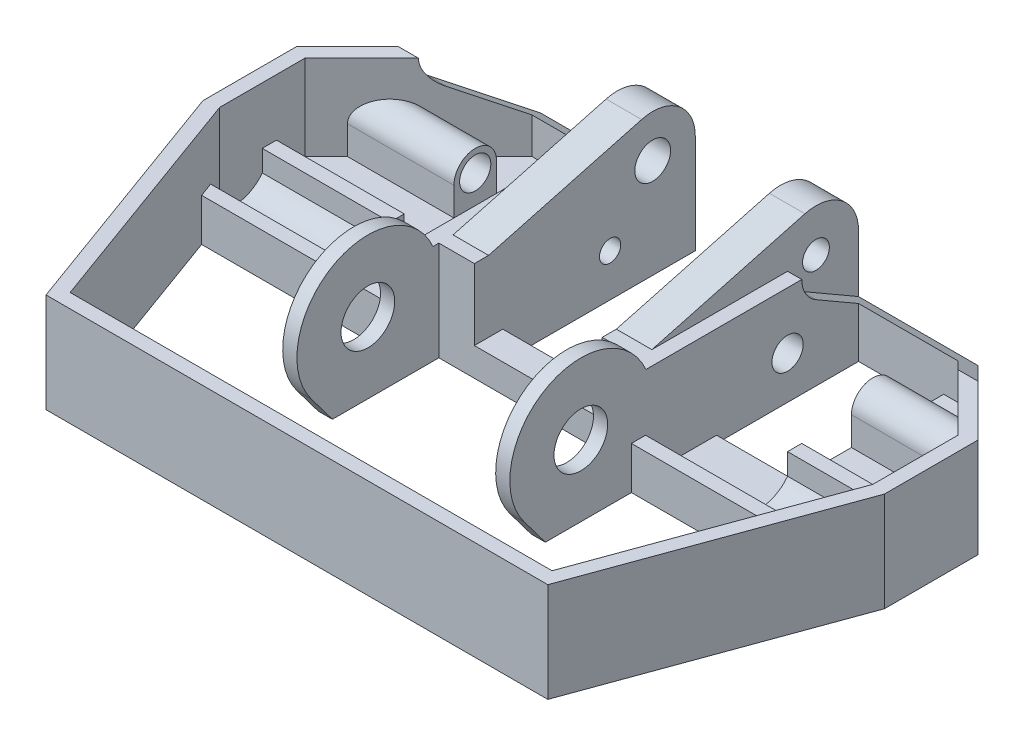
SolidWorks part; units mm, degrees
material "ABS"
ref_plane "Front Plane" through (0, 0, 0) normal (0, 0, 1) x (1, 0, 0)
ref_plane "Top Plane" through (0, 0, 0) normal (0, 1, 0) x (1, 0, 0)
ref_plane "Right Plane" through (0, 0, 0) normal (1, 0, 0) x (0, 0, -1)
sketch "Sketch1" plane through (0, 0, 0) normal (1, 0, 0) x (0, 0, -1)
  line L0 (9.525, -22.225) -> (9.525, 0)
  line L1 (-2.4719, 9.1987) -> (-36.703, 0)
  line L2 (-36.703, 0) -> (-36.703, -22.225)
  line L3 (-36.703, -22.225) -> (9.525, -22.225)
  circle A0 centre (0, 0) radius 20.6375 construction
  arc A1 (9.525, 0) -> (-2.4719, 9.1987) centre (0, 0) ccw
  point P5 (-31.75, -9.7269)
  point P10 (0, -20.6375)
  dimension "D1" = 41.275
  dimension "D2" = 9.525
  dimension "D3" = 22.225
  dimension "D4" = 46.228
  dimension "D5" = 1.5875
extrude "Boss-Extrude1" add sketch "Sketch1" along normal mid plane 44.45
ref_plane "Plane1" through (0, 0, 0) normal (0, -1, 0) x (-1, 0, 0)
sketch "Sketch3" plane through (0, 0, 0) normal (0, -1, 0) x (-1, 0, 0)
  line L0 (22.225, 9.525) -> (22.225, -36.703)
  line L1 (22.225, -36.703) -> (-22.225, -36.703)
  line L2 (-22.225, -36.703) -> (-22.225, 9.525)
  line L3 (-22.225, 9.525) -> (-48.9401, 9.525)
  line L4 (-48.9401, 9.525) -> (-76.2, -17.7349)
  line L5 (-76.2, -17.7349) -> (-76.2, -38.6598)
  line L6 (-76.2, -38.6598) -> (-56.1113, -93.853)
  line L7 (-56.1113, -93.853) -> (56.1113, -93.853)
  line L8 (56.1113, -93.853) -> (76.2, -38.6598)
  line L9 (76.2, -38.6598) -> (76.2, -17.7349)
  line L10 (76.2, -17.7349) -> (48.9401, 9.525)
  line L11 (48.9401, 9.525) -> (22.225, 9.525)
  line L12 (73.025, -19.05) -> (47.625, 6.35)
  line L13 (47.625, 6.35) -> (25.4, 6.35)
  line L14 (25.4, 6.35) -> (25.4, -49.403)
  line L15 (22.225, -39.878) -> (-22.225, -39.878)
  line L16 (-25.4, -49.403) -> (-25.4, 6.35)
  line L17 (-25.4, 6.35) -> (-47.625, 6.35)
  line L18 (-47.625, 6.35) -> (-73.025, -19.05)
  line L19 (-73.025, -19.05) -> (-73.025, -38.1)
  line L20 (-73.025, -38.1) -> (-53.8882, -90.678)
  line L21 (-53.8882, -90.678) -> (53.8882, -90.678)
  line L22 (-25.4, -49.403) -> (-22.225, -49.403)
  line L23 (73.025, -38.1) -> (73.025, -19.05)
  line L24 (22.225, -49.403) -> (25.4, -49.403)
  line L27 (22.225, -39.878) -> (22.225, -49.403)
  line L28 (-22.225, -39.878) -> (-22.225, -49.403)
  line L30 (25.4, -39.878) -> (-25.4, -39.878) construction
  line L31 (53.8882, -90.678) -> (73.025, -38.1)
  line L32 (53.8882, -90.678) -> (73.025, -38.1) construction
  line L34 (-73.025, -38.1) -> (-53.8882, -90.678) construction
  line L35 (25.4, 6.35) -> (25.4, -39.878) construction
  line L36 (-25.4, -39.878) -> (-25.4, 6.35) construction
  point P5 (0, -93.853)
  point P21 (0, 0)
  dimension "D1" = 20
  dimension "D2" = 22.225
  dimension "D3" = 3.175
  dimension "D4" = 47.625
  dimension "D5" = 50.8
  dimension "D6" = 9.525
  dimension "D8" = 44.45
  dimension "D9" = 45
extrude "Boss-Extrude2" add sketch "Sketch3" along normal up to surface (22.225 mm away) up to face at (0, -22.225, 13.589)
sketch "Sketch4" plane through (0, -22.225, 0) normal (0, -1, 0) x (1, 0, 0)
  line L0 (48.9401, -9.525) -> (-48.9401, -9.525) construction
  line L1 (-14.2875, -9.525) -> (14.2875, -9.525)
  line L2 (-14.2875, -9.525) -> (-14.2875, 33.528)
  line L3 (-14.2875, 33.528) -> (14.2875, 33.528)
  line L4 (14.2875, -9.525) -> (14.2875, 33.528)
  line L5 (22.225, 39.878) -> (-22.225, 39.878) construction
  point P6 (0, 33.528)
  dimension "D1" = 28.575
  dimension "D2" = 6.35
extrude "Cut-Extrude1" cut sketch "Sketch4" against normal through all
sketch "Sketch5" plane through (0, 0, 0) normal (1, 0, 0) x (0, 0, -1)
  line L0 (6.35, -22.225) -> (6.35, 0) construction
  line L1 (-17.7349, -22.225) -> (9.525, -22.225) construction
  circle A0 centre (-9.525, -12.7) radius 3.175
  point P6 (0, 0)
  dimension "D1" = 6.35
  dimension "D2" = 15.875
  dimension "D3" = 9.525
sketch "Sketch6" plane through (0, 0, 0) normal (0, 1, 0) x (1, 0, 0)
  line L0 (-22.225, 9.525) -> (-22.225, -2.4719) construction
  line L1 (-22.225, 4) -> (17.775, 4)
  line L2 (22.225, -2.4719) -> (22.225, 9.525) construction
  line L3 (-22.225, 0) -> (22.225, 0)
  line L4 (17.775, 4) -> (17.775, 3)
  line L5 (22.225, -2.4719) -> (22.225, 9.525) construction
  line L6 (-47.625, 6.35) -> (-25.4, 6.35) construction
  line L7 (-22.225, 0) -> (-88.5794, 0)
  line L8 (17.775, 3) -> (22.225, 3)
  line L10 (-22.225, 4) -> (-22.225, 6.35)
  line L11 (-22.225, 6.35) -> (-88.5794, 6.35)
  line L12 (-88.5794, 0) -> (-88.5794, 6.35)
  line L14 (22.225, 0) -> (78.8074, 0)
  line L15 (22.225, 3) -> (22.225, 6.35)
  line L16 (22.225, 6.35) -> (78.8074, 6.35)
  line L17 (78.8074, 0) -> (78.8074, 6.35)
  line L18 (25.4, 6.35) -> (47.625, 6.35) construction
  point P1 (0, 0)
  point P9 (0, 0)
  point P19 (-25.4294, 9.525)
  point P20 (-25.4, 0)
  point P21 (-25.4, 6.35)
  point P22 (-64.9741, 0)
  point P23 (-58.4654, -0.0002)
  point P24 (22.225, 0)
  point P25 (22.225, 9.525)
  point P28 (0, 0)
  point P29 (-113.2509, 0)
  point P30 (108.8149, 0)
  point P31 (25.4, 0)
  point P32 (37.9723, 6.35)
  point P35 (58.5203, -0.0552)
  point P36 (-25.4, 6.35)
  point P37 (-88.5794, 6.35)
  point P38 (60.3046, 0)
  point P39 (25.4, 0)
  point P40 (78.8074, 0)
  dimension "D1" = 4
  dimension "D2" = 3
  dimension "D3" = 40
revolve "Cut-Revolve1" cut sketch "Sketch6" angle 360 about L3
sketch "Sketch9" plane through (0, 0, 33.528) normal (0, 0, -1) x (-1, 0, 0)
  line L0 (-14.2875, 0.8532) -> (-14.2875, -15.875)
  line L1 (-14.2875, -15.875) -> (14.2875, -15.875)
  line L2 (14.2875, -15.875) -> (14.2875, 0.8532)
  line L3 (-14.2875, -22.225) -> (14.2875, -22.225) construction
  line L4 (14.2875, 0.8532) -> (-14.2875, 0.8532)
  point P8 (-11.652, -23.8125)
  dimension "D1" = 28.575
  dimension "D2" = 6.35
extrude "Cut-Extrude4" cut sketch "Sketch9" against normal up to next
sketch "Sketch10" plane through (25.4, 0, 0) normal (1, 0, 0) x (0, 0, -1)
  line L0 (-28.575, -17.4625) -> (-28.575, -12.7)
  line L1 (-41.275, -12.7) -> (-41.275, -17.4625)
  line L2 (6.35, -22.225) -> (6.35, 0) construction
  line L4 (-93.853, -22.225) -> (-38.6598, -22.225) construction
  line L5 (-44.45, -22.225) -> (-25.4, -22.225)
  line L6 (-44.45, -22.225) -> (-44.45, -12.7)
  line L7 (-44.45, -12.7) -> (-41.275, -12.7)
  line L8 (-25.4, -22.225) -> (-25.4, -12.7)
  line L9 (-28.575, -12.7) -> (-25.4, -12.7)
  arc A0 (-41.275, -17.4625) -> (-28.575, -17.4625) centre (-34.925, -12.7) ccw
  point P3 (0, 0)
  point P4 (-25.4, -26.0716)
  point P9 (-39.9499, -30.1625)
  point P10 (-38.1, -25.6652)
  point P11 (0, 0)
  dimension "D1" = 12.7
  dimension "D2" = 15.875
  dimension "D3" = 34.925
  dimension "D5" = 19.05
  dimension "D6" = 9.525
extrude "Boss-Extrude3" add sketch "Sketch10" along normal up to next
mirror "Mirror1" about plane through (0, 0, 0) normal (1, 0, 0) of "Boss-Extrude3"
sketch "Sketch11" plane through (0, -12.7, 0) normal (0, 1, 0) x (1, 0, 0)
  line L0 (-25.4, -28.575) -> (-25.4, -41.275) construction
  line L1 (-25.4, -34.925) -> (-44.45, -34.925)
  line L2 (-25.4, -34.925) -> (-25.4, -15.875)
  line L3 (-25.4, -15.875) -> (-44.45, -15.875)
  line L4 (-44.45, -34.925) -> (-44.45, -15.875)
  line L5 (25.4, -41.275) -> (25.4, -28.575) construction
  line L6 (25.4, -34.925) -> (44.45, -34.925)
  line L7 (25.4, -34.925) -> (25.4, -15.875)
  line L8 (25.4, -15.875) -> (44.45, -15.875)
  line L9 (44.45, -34.925) -> (44.45, -15.875)
  dimension "D1" = 19.05
extrude "Cut-Extrude5" cut sketch "Sketch11" against normal blind 7.9375
ref_plane "Plane2" through (0, -12.7, 0) normal (0, -1, 0) x (-1, 0, 0)
sketch "Sketch18" plane through (-44.45, 0, 0) normal (1, 0, 0) x (0, 0, -1)
  line L0 (-25.4, -22.225) -> (6.35, -22.225)
  line L1 (6.35, -22.225) -> (6.35, -19.05)
  line L2 (6.35, -22.225) -> (6.35, 0) construction
  line L3 (6.35, -19.05) -> (-4.7625, -19.05)
  line L4 (-4.7625, -19.05) -> (-4.7625, -12.7)
  line L5 (-56.8579, -12.7) -> (56.8579, -12.7) construction
  line L6 (-14.2875, -12.7) -> (-14.2875, -19.05)
  line L7 (-14.2875, -19.05) -> (-25.4, -19.05)
  line L8 (-25.4, -12.7) -> (-25.4, -22.225) construction
  line L9 (-25.4, -19.05) -> (-25.4, -22.225)
  arc A0 (-4.7625, -12.7) -> (-14.2875, -12.7) centre (-9.525, -12.7) ccw
  point P17 (-6.1927, -19.05)
  point P18 (-9.525, -12.7)
  dimension "D1" = 4.7625
  dimension "D2" = 3.175
extrude "Boss-Extrude6" add sketch "Sketch18" against normal up to next
mirror "Mirror3" about plane through (0, 0, 0) normal (1, 0, 0) of "Boss-Extrude6"
sketch "Sketch14" plane through (0, -12.7, 0) normal (0, -1, 0) x (-1, 0, 0)
  line L0 (-14.2875, 9.525) -> (-14.2875, -33.528) construction
  line L1 (-73.7019, -6.0325) -> (-19.05, -6.0325)
  line L2 (-73.7019, -6.0325) -> (-73.7019, -9.525)
  line L3 (-73.7019, -9.525) -> (-14.2875, -9.525)
  line L4 (-19.05, -6.0325) -> (-19.05, -7.1438)
  line L5 (0, 0) -> (0, 30.2993) construction
  line L6 (14.2875, -9.525) -> (14.2875, -7.1438)
  line L7 (-19.05, -7.1438) -> (-14.2875, -7.1438)
  line L8 (-14.2875, -9.525) -> (-14.2875, -7.1438)
  line L10 (19.05, -7.1438) -> (14.2875, -7.1438)
  line L11 (19.05, -6.0325) -> (19.05, -7.1438)
  line L12 (73.7019, -9.525) -> (14.2875, -9.525)
  line L13 (73.7019, -6.0325) -> (73.7019, -9.525)
  line L14 (73.7019, -6.0325) -> (19.05, -6.0325)
  point P12 (-37.2353, -9.525)
  point P13 (-21.2207, -7.1438)
  point P17 (-25.4, -6.0325)
  point P21 (-73.7019, -6.0325)
  dimension "D1" = 3.4925
  dimension "D2" = 4.7625
  dimension "D3" = 2.3812
revolve "Cut-Revolve2" cut sketch "Sketch14" angle 360 about L3
sketch "Sketch15" plane through (-22.225, 0, 0) normal (1, 0, 0) x (0, 0, -1)
  line L0 (-93.853, -22.225) -> (-38.6598, -22.225) construction
  line L1 (-39.878, -22.225) -> (-39.878, 0) construction
  line L2 (-39.878, -22.225) -> (-63.6852, -22.225)
  line L3 (-63.6852, -22.225) -> (-68.4479, -15.8818)
  line L4 (-39.878, -6.35) -> (-39.878, -22.225)
  arc A0 (-39.878, -6.35) -> (-68.4479, -15.8818) centre (-55.753, -6.35) ccw
  point P13 (-35.7893, -30.1625)
  dimension "D1" = 31.75
  dimension "D2" = 53.099
extrude "Boss-Extrude4" add sketch "Sketch15" against normal blind 3.175
mirror "Mirror2" about plane through (0, 0, 0) normal (1, 0, 0) of "Boss-Extrude4"
sketch "Sketch19" plane through (-25.4, 0, 0) normal (-1, 0, 0) x (0, 0, 1)
  circle A0 centre (55.753, -6.35) radius 6
  dimension "D1" = 12
extrude "Cut-Extrude6" cut sketch "Sketch19" against normal up to surface (50.8 mm away) up to face at (25.4, -13.901, 33.343)
sketch "Sketch20" plane through (-22.225, 0, 0) normal (-1, 0, 0) x (0, 0, 1)
  line L0 (3.175, -5.4993) -> (-9.525, -12.8316)
  line L1 (-9.525, -22.225) -> (-9.525, 0) construction
  line L2 (-9.525, -12.8316) -> (-9.525, 0)
  line L3 (-112.6445, 0) -> (112.6445, 0) construction
  line L4 (-9.525, 0) -> (3.175, 0)
  line L5 (3.175, 0) -> (3.175, -5.4993)
  arc A0 (-6.35, 0) -> (6.35, 0) centre (0, 0) ccw construction
  point P4 (0, -8.1871)
  point P10 (3.3885, -6.4779)
  point P14 (0, 0)
  point P16 (3.2996, -5.4254)
  dimension "D1" = 60
extrude "Cut-Extrude7" cut sketch "Sketch20" along normal through all
mirror "Mirror4" about plane through (0, 0, 0) normal (1, 0, 0) of "Cut-Extrude7"
